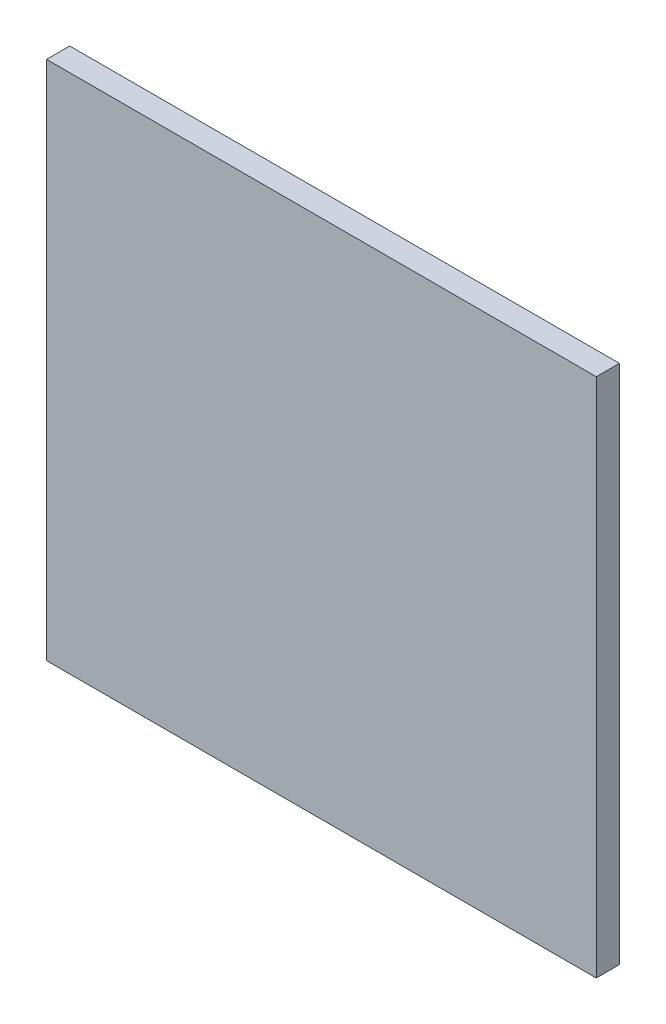
SolidWorks part; units mm, degrees
ref_plane "Front Plane" through (0, 0, 0) normal (0, 0, 1) x (1, 0, 0)
ref_plane "Top Plane" through (0, 0, 0) normal (0, 1, 0) x (1, 0, 0)
ref_plane "Right Plane" through (0, 0, 0) normal (1, 0, 0) x (0, 0, -1)
sketch "Sketch1" plane through (0, 0, 0) normal (0, 0, 1) x (1, 0, 0)
  line L1 (0, 0) -> (38, 0)
  line L2 (0, 0) -> (0, -36)
  line L3 (0, -36) -> (38, -36)
  line L4 (38, 0) -> (38, -36)
  dimension "D1" = 38
  dimension "D2" = 36
extrude "Boss-Extrude1" add sketch "Sketch1" along normal blind 1.6
